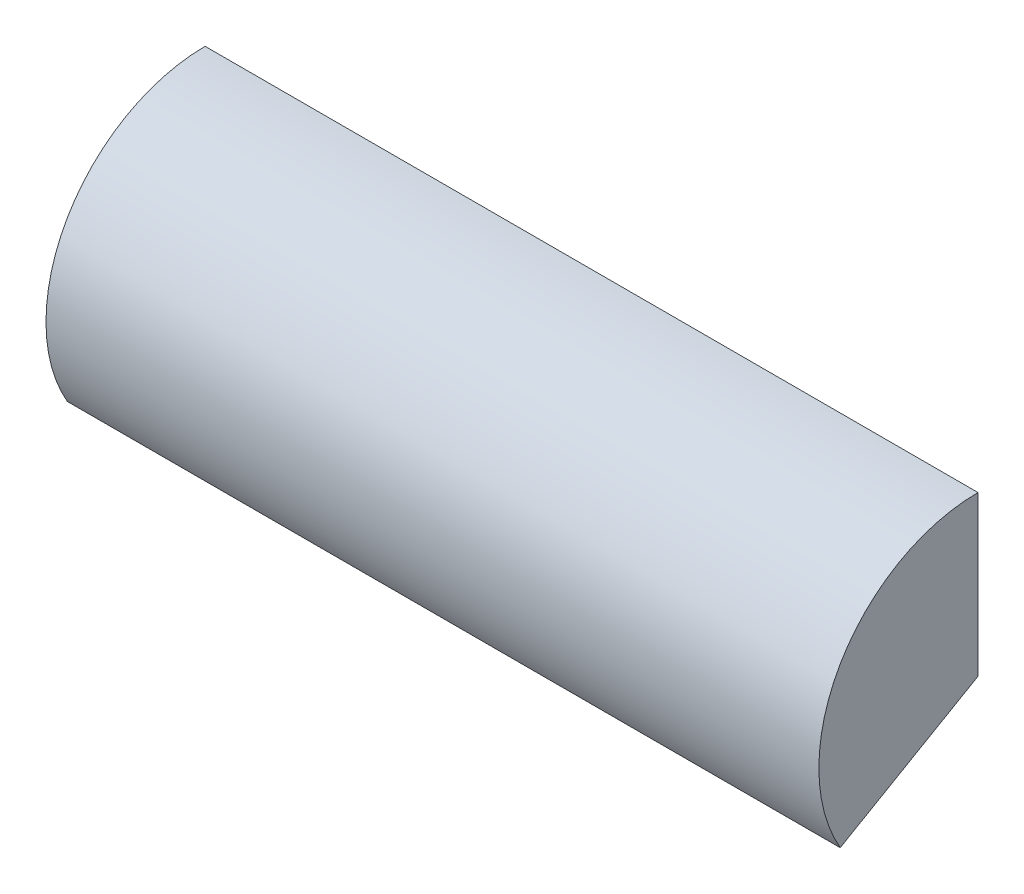
SolidWorks part; units mm, degrees
material "Expanded Polystyrene (EPS)"
ref_plane "Front Plane" through (0, 0, 0) normal (1, 0, 0) x (0, 1, 0)
ref_plane "Top Plane" through (0, 0, 0) normal (0, 0, 1) x (0, 1, 0)
ref_plane "Right Plane" through (0, 0, 0) normal (0, 1, 0) x (-1, 0, 0)
sketch "Sketch1" plane through (0, 0, 0) normal (0, 0, 1) x (0, 1, 0)
  line L1 (0, 0) -> (44.45, 0)
  line L2 (0, 0) -> (0, 215.9)
  line L3 (0, 215.9) -> (44.45, 215.9)
  line L4 (44.45, 0) -> (44.45, 215.9)
  dimension "D1" = 215.9
  dimension "D2" = 44.45
revolve "Revolve1" add sketch "Sketch1" angle 120 about L2
sketch "Sketch21" plane through (0, 0, 0) normal (0, 0, -1) x (-1, 0, 0)
  line L1 (215.9, 0) -> (0, 0) construction
  line L2 (71.8627, 22.5006) -> (63.8098, 22.5005) construction
  line L3 (193.3616, 1.4899) -> (73.3627, 22.4963) construction
  line L4 (215.9, 0) -> (0, 0)
  line L5 (71.8627, 22.5006) -> (63.8098, 22.5005)
  line L6 (193.3616, 1.4899) -> (73.3627, 22.4963)
  line L7 (193.3616, 1.4899) -> (193.3615, -0.0101)
  line L8 (71.8627, 22.5006) -> (73.3627, 22.4963)
  line L9 (3.81, 0) -> (3.4091, 11.4291) construction
  line L10 (3.4091, 11.4291) -> (63.8098, 22.5005) construction
  spline S0 degree 2 poles (3.81, 0) (3.4091, 11.4291) (63.8098, 22.5005) knots 0 0 0 1 1 1
  point P9 (3.4091, 11.4291)
revolve "Cut-Revolve21" cut sketch "Sketch21" angle 360 about L4
